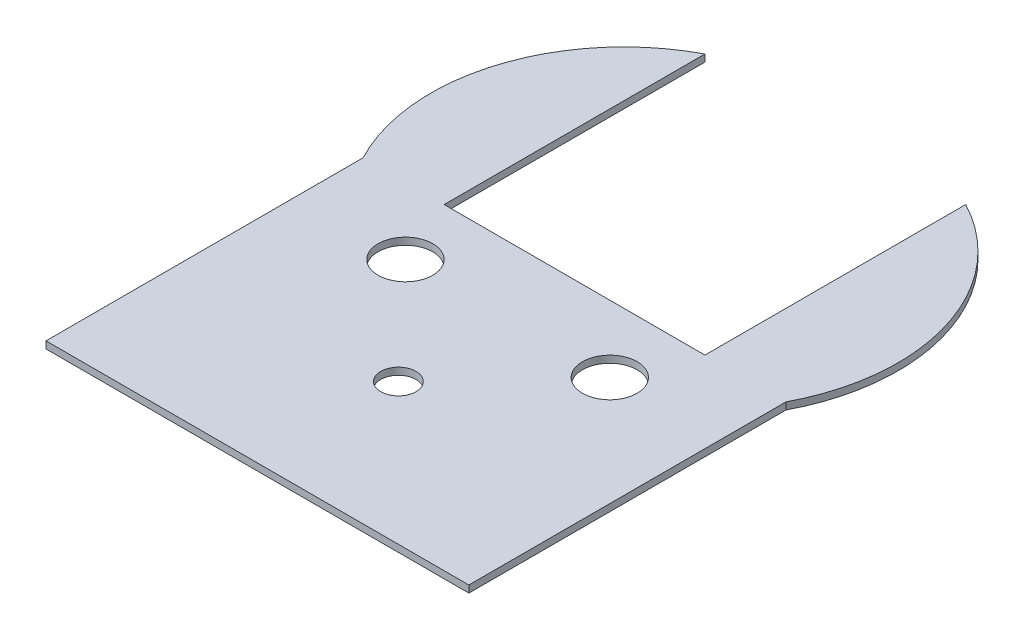
SolidWorks part; units mm, degrees
ref_plane "Front Plane" through (0, 0, 0) normal (0, 0, 1) x (1, 0, 0)
ref_plane "Top Plane" through (0, 0, 0) normal (0, 1, 0) x (1, 0, 0)
ref_plane "Right Plane" through (0, 0, 0) normal (1, 0, 0) x (0, 0, -1)
sketch "Sketch1" plane through (0, 0, 0) normal (0, 1, 0) x (1, 0, 0)
  line L0 (-19.8017, 0) -> (17.1983, 0)
  line L1 (-19.8017, 0) -> (-19.8017, 37)
  line L2 (17.1983, 0) -> (17.1983, 37)
  line L3 (-19.8017, 0) -> (-31.3017, 0) construction
  line L4 (17.1983, 0) -> (5.5712, 0) construction
  line L8 (17.1983, 0) -> (28.6983, 0) construction
  line L9 (-31.3017, 0) -> (-31.3017, -45)
  line L10 (-31.3017, -45) -> (28.6983, -45)
  line L11 (28.6983, -45) -> (28.6983, 0)
  arc A4 (-19.8017, 37) -> (-31.3017, 0) centre (-7.0517, 12.75) ccw
  arc A5 (17.1983, 37) -> (28.6983, 0) centre (4.4483, 12.75) cw
extrude "Boss-Extrude1" add sketch "Sketch1" along normal blind 1
sketch "Sketch2" plane through (0, 1, 0) normal (0, 1, 0) x (1, 0, 0)
  line L0 (-1.3017, -45) -> (-1.3017, -5) construction
  line L2 (-31.3017, -45) -> (28.6983, -45) construction
  circle A1 centre (-1.3017, -25) radius 2.5
extrude "Cut-Extrude1" cut sketch "Sketch2" against normal blind 20
sketch "Sketch3" plane through (0, 0, 0) normal (0, -1, 0) x (1, 0, 0)
  line L0 (28.6983, 45) -> (28.6983, 0) construction
  line L1 (15.6983, 7) -> (10.6983, 7)
  line L2 (15.6983, 7) -> (15.6983, 12)
  line L3 (15.6983, 12) -> (10.6983, 12)
  line L4 (10.6983, 7) -> (10.6983, 12)
  line L5 (17.1983, 0) -> (-19.8017, 0) construction
  line L6 (-1.3017, 0) -> (-1.3017, 45) construction
  line L8 (-13.3017, 7) -> (-13.3017, 12)
  line L9 (-18.3017, 12) -> (-13.3017, 12)
  line L10 (-18.3017, 7) -> (-18.3017, 12)
  line L11 (-18.3017, 7) -> (-13.3017, 7)
  dimension "D1" = 13
  dimension "D2" = 7
  dimension "D3" = 5
  dimension "D4" = 30
extrude "Cut-Extrude2" cut sketch "Sketch3" against normal blind 10
sketch "Sketch4" plane through (0, 0, 0) normal (0, -1, 0) x (1, 0, 0)
  line L0 (13.1983, 7) -> (13.1983, 12) construction
  line L1 (10.6983, 7) -> (15.6983, 7) construction
  line L2 (15.6983, 12) -> (10.6983, 12) construction
  line L3 (15.6983, 9.5) -> (10.6983, 9.5) construction
  line L4 (15.6983, 7) -> (15.6983, 12) construction
  line L5 (10.6983, 12) -> (10.6983, 7) construction
  line L6 (-1.3017, 0) -> (-1.3017, 45) construction
  line L7 (17.1983, 0) -> (-19.8017, 0) construction
  line L8 (-31.3017, 45) -> (28.6983, 45) construction
  line L9 (28.6983, 45) -> (28.6983, 0) construction
  circle A0 centre (13.1983, 9.5) radius 3.8814
  circle A1 centre (-15.8017, 9.5) radius 3.8814
  dimension "D1" = 30
extrude "Cut-Extrude3" cut sketch "Sketch4" against normal blind 10
